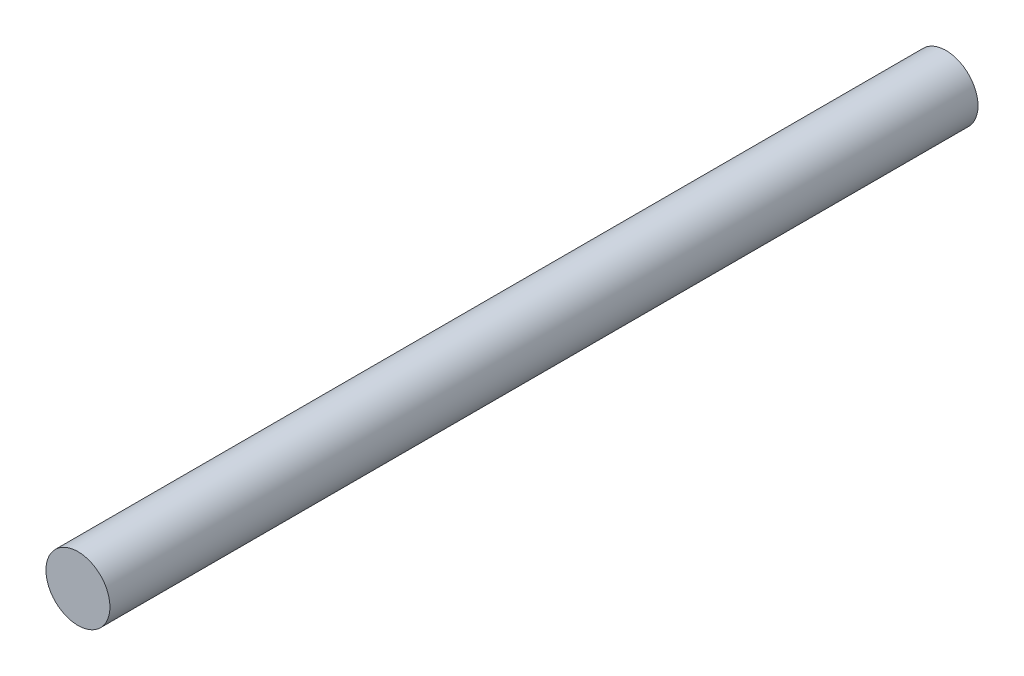
SolidWorks part; units mm, degrees
material "AISI 304"
ref_plane "Front Plane" through (0, 0, 0) normal (0, 0, 1) x (1, 0, 0)
ref_plane "Top Plane" through (0, 0, 0) normal (0, 1, 0) x (1, 0, 0)
ref_plane "Right Plane" through (0, 0, 0) normal (1, 0, 0) x (0, 0, -1)
sketch "Sketch1" plane through (0, 0, 0) normal (0, 0, 1) x (1, 0, 0)
  circle A0 centre (0, 0) radius 4
  dimension "D1" = 8
extrude "Boss-Extrude1" add sketch "Sketch1" along normal blind 108.5
